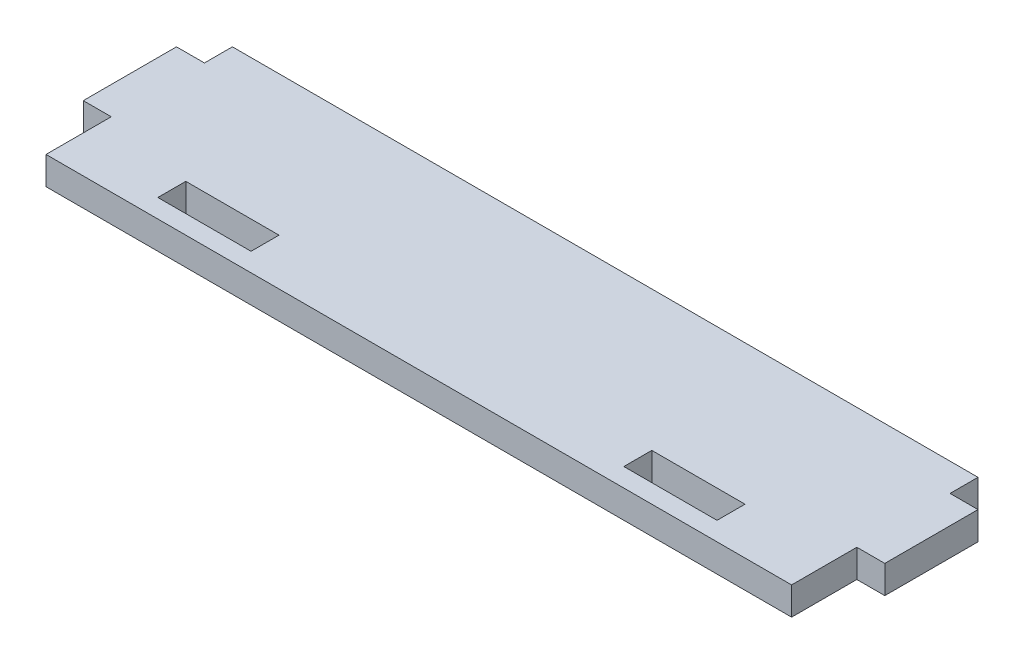
SolidWorks part; units mm, degrees
material "ABS"
ref_plane "Front Plane" through (0, 0, 0) normal (0, 0, 1) x (1, 0, 0)
ref_plane "Top Plane" through (0, 0, 0) normal (0, 1, 0) x (1, 0, 0)
ref_plane "Right Plane" through (0, 0, 0) normal (1, 0, 0) x (0, 0, -1)
sketch "Sketch1" plane through (0, 0, 0) normal (0, 1, 0) x (1, 0, 0)
  line L0 (0, 17) -> (0, 20)
  line L1 (0, 0) -> (80, 0)
  line L2 (0, 0) -> (0, 7)
  line L3 (0, 20) -> (80, 20)
  line L4 (80, 0) -> (80, 7)
  line L5 (80, 17) -> (83, 17)
  line L7 (80, 7) -> (83, 7)
  line L8 (83, 17) -> (83, 7)
  line L9 (0, 17) -> (-3, 17)
  line L11 (0, 7) -> (-3, 7)
  line L12 (-3, 17) -> (-3, 7)
  line L13 (80, 17) -> (80, 20)
  line L15 (10, 5) -> (20, 5)
  line L16 (10, 5) -> (10, 2)
  line L17 (10, 2) -> (20, 2)
  line L18 (20, 5) -> (20, 2)
  line L19 (60, 5) -> (70, 5)
  line L20 (60, 5) -> (60, 2)
  line L21 (60, 2) -> (70, 2)
  line L22 (70, 5) -> (70, 2)
  dimension "D1" = 20
  dimension "D2" = 80
  dimension "D3" = 3
  dimension "D4" = 10
  dimension "D5" = 7
  dimension "D6" = 7
  dimension "D7" = 10
  dimension "D8" = 3
  dimension "D9" = 10
  dimension "D10" = 10
  dimension "D11" = 3
  dimension "D12" = 3
  dimension "D13" = 2
  dimension "D14" = 2
  dimension "D15" = 10
  dimension "D16" = 40
extrude "Boss-Extrude1" add sketch "Sketch1" along normal blind 3
